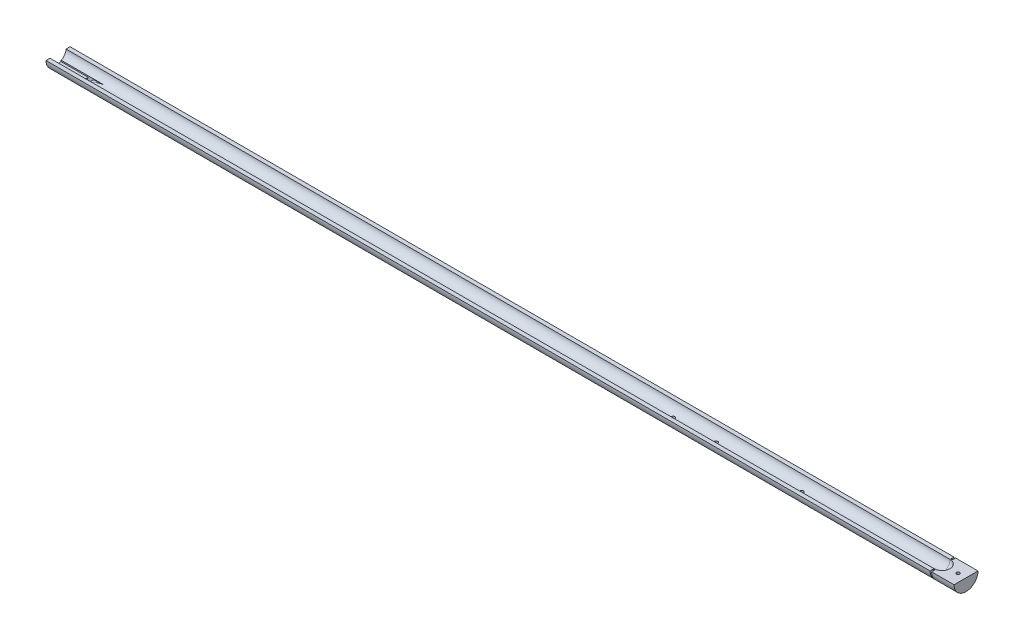
SolidWorks part; units mm, degrees
ref_plane "Front Plane" through (0, 0, 0) normal (0, 0, 1) x (1, 0, 0)
ref_plane "Top Plane" through (0, 0, 0) normal (0, 1, 0) x (1, 0, 0)
ref_plane "Right Plane" through (0, 0, 0) normal (1, 0, 0) x (0, 0, -1)
sketch "Sketch1" plane through (0, 0, 0) normal (0, 1, 0) x (1, 0, 0)
  line L1 (0, 0) -> (1803.4, 0)
  line L2 (0, 0) -> (0, 57.15)
  line L3 (0, 57.15) -> (1803.4, 57.15)
  line L4 (1803.4, 0) -> (1803.4, 57.15)
  dimension "D1" = 1803.4
  dimension "D2" = 57.15
extrude "wood block" add sketch "Sketch1" along normal blind 28.575
ref_plane "Plane1" through (0, 0, -28.575) normal (0, 0, 1) x (1, 0, 0)
sketch "Sketch2" plane through (0, 0, -28.575) normal (0, 0, 1) x (1, 0, 0)
  line L0 (1771.65, 28.575) -> (-15.875, 28.575)
  line L1 (0, 28.575) -> (1803.4, 28.575) construction
  line L2 (0, 12.7) -> (1755.775, 12.7)
  line L4 (1803.4, 28.575) -> (1803.4, 0) construction
  arc A0 (-15.875, 28.575) -> (0, 12.7) centre (0, 28.575) ccw
  arc A1 (1755.775, 12.7) -> (1771.65, 28.575) centre (1755.775, 28.575) ccw
  point P10 (0, 12.7)
  dimension "D1" = 15.875
  dimension "extralength" = 31.75
revolve "Inner Bore" cut sketch "Sketch2" angle 360 about L0
ref_axis "Axis1" through (0, 28.575, -28.575) along (1, 0, 0)
sketch "Sketch5" plane through (0, 0, -28.575) normal (0, 0, 1) x (1, 0, 0)
  line L0 (53.975, 28.575) -> (53.975, 12.1285)
  line L1 (0, 12.7) -> (1755.775, 12.7) construction
  line L3 (53.975, 0) -> (64.135, 0)
  line L4 (64.135, 0) -> (64.135, 12.1285) construction
  line L6 (64.135, 28.575) -> (53.975, 28.575)
  line L10 (0, 4.7625) -> (159.6887, 4.7625) construction
  line L12 (0, 12.7) -> (159.6887, 12.7) construction
  line L13 (64.135, 12.1285) -> (97.4578, 0)
  line L14 (97.4578, 0) -> (64.135, 0)
  line L15 (64.135, 12.1285) -> (64.135, 28.575)
  line L16 (53.975, 12.1285) -> (48.9512, 0)
  line L17 (48.9512, 0) -> (53.975, 0)
  line L18 (53.975, 12.1285) -> (53.975, 0) construction
  line L29 (0, 0) -> (1803.4, 0) construction
  line L34 (0, 28.575) -> (0, 0) construction
  line L35 (0, 28.575) -> (1803.4, 28.575) construction
  line L36 (0, 0) -> (1803.4, 0) construction
  line L37 (64.135, 12.1285) -> (53.975, 12.1285) construction
  point P2 (53.975, 28.575)
  point P3 (53.975, 12.7)
  point P4 (0, 0)
  point P5 (159.6887, 12.7)
  point P6 (1755.775, 28.575)
  point P11 (0, 28.575)
  point P12 (1803.4, 28.575)
  point P21 (53.975, 28.575)
  point P22 (1771.65, 28.575)
  point P23 (1755.775, 28.575)
  point P24 (53.975, 28.575)
  point P25 (38.1, 28.575)
  point P26 (53.975, 28.575)
  point P27 (1755.775, 28.575)
  point P28 (0, 28.575)
  point P29 (0, 0)
  point P30 (1803.4, 28.575)
  point P31 (1803.4, 0)
  point P32 (1803.4, 28.575)
  point P33 (1803.4, 0)
  point P34 (0, 28.575)
  point P35 (0, 0)
  point P36 (1803.4, 28.575)
  point P37 (0, 28.575)
  point P38 (1803.4, 0)
  point P39 (0, 0)
  point P40 (0, 0)
  point P41 (1803.4, 0)
  point P42 (1755.775, 28.575)
  point P43 (1755.775, 12.7)
  point P46 (1755.775, 28.575)
  point P47 (53.975, 28.575)
  point P48 (1771.65, 28.575)
  point P49 (1755.775, 28.575)
  point P50 (53.975, 28.575)
  point P51 (38.1, 28.575)
  point P52 (53.975, 28.575)
  point P53 (1755.775, 28.575)
  dimension "D1" = 10.16
  dimension "D2" = 53.975
  dimension "D3" = 22.5
  dimension "D4" = 20
  dimension "D5" = 7.366
  dimension "D6" = 23.8125
extrude "fipple" cut sketch "Sketch5" against normal mid plane 12.7
sketch "Sketch3" plane through (0, 0, 0) normal (0, 1, 0) x (1, 0, 0)
  line L122 (64.135, 34.925) -> (64.135, 22.225) construction
  line L123 (1476.629, 28.575) -> (1306.449, 28.575) construction
  line L124 (1306.449, 28.575) -> (1221.359, 28.575) construction
  line L125 (1221.359, 28.575) -> (64.135, 28.575) construction
  circle A0 centre (1476.629, 28.575) radius 3.81
  circle A1 centre (1306.449, 28.575) radius 3.81
  circle A2 centre (1221.359, 28.575) radius 3.81
  point P2 (-6.496, 28.575)
  point P3 (6.496, 28.575)
  point P10 (53.975, 22.225)
  point P11 (74.081, 22.225)
  point P12 (53.975, 34.925)
  point P13 (64.135, 34.925)
  point P14 (64.135, 34.925)
  point P15 (64.135, 22.225)
  point P16 (53.975, 22.225)
  point P17 (64.135, 22.225)
  point P18 (1724.025, 44.45)
  point P19 (53.975, 44.45)
  point P20 (1724.025, 28.575)
  point P21 (1724.025, 12.7)
  point P22 (1724.025, 44.45)
  point P23 (53.975, 28.575)
  point P24 (53.975, 44.45)
  point P25 (53.975, 12.7)
  point P26 (53.975, 12.7)
  point P27 (1724.025, 12.7)
  point P28 (1803.4, 4.7625)
  point P29 (1803.4, 52.3875)
  point P30 (0, 52.3875)
  point P31 (0, 4.7625)
  point P32 (53.975, 12.7)
  point P33 (53.975, 22.225)
  point P34 (53.975, 22.225)
  point P35 (53.975, 34.925)
  point P36 (53.975, 34.925)
  point P37 (53.975, 44.45)
  point P38 (1724.025, 12.7)
  point P39 (1724.025, 44.45)
  point P40 (64.135, 34.925)
  point P41 (64.135, 22.225)
  point P42 (74.081, 34.925)
  point P43 (64.135, 34.925)
  point P44 (74.081, 22.225)
  point P45 (64.135, 22.225)
  point P46 (1803.4, 4.7625)
  point P47 (0, 4.7625)
  point P48 (0, 52.3875)
  point P49 (1803.4, 52.3875)
  point P50 (53.975, 34.925)
  point P51 (74.081, 34.925)
  point P52 (74.081, 22.225)
  point P53 (74.081, 34.925)
  point P54 (-54.3985, 28.575)
  point P55 (76.4501, 28.575)
  point P56 (11.0258, 4.7625)
  point P57 (11.0258, 52.3875)
  point P58 (11.0258, 28.575)
  point P59 (53.975, 22.225)
  point P60 (53.975, 34.925)
  point P61 (1803.4, 4.7625)
  point P62 (1803.4, 52.3875)
  point P63 (0, 52.3875)
  point P64 (0, 4.7625)
  point P65 (0, 0)
  point P66 (1803.4, 0)
  point P67 (0, 0)
  point P68 (0, 57.15)
  point P69 (0, 57.15)
  point P70 (1803.4, 57.15)
  point P71 (1803.4, 0)
  point P72 (1803.4, 57.15)
  point P73 (1739.9, 28.575)
  point P74 (38.1, 28.575)
  point P75 (0, 28.575)
  point P76 (1803.4, 28.575)
  point P77 (53.975, 28.575)
  point P78 (1724.025, 28.575)
  point P79 (1803.4, 28.575)
  point P80 (0, 28.575)
  point P81 (53.975, 28.575)
  point P82 (64.135, 28.575)
  point P83 (64.135, 28.575)
  point P84 (53.975, 28.575)
  point P85 (0, 28.575)
  point P86 (1803.4, 28.575)
  point P87 (0, 28.575)
  point P88 (159.6887, 28.575)
  point P89 (0, 28.575)
  point P90 (159.6887, 28.575)
  point P91 (64.135, 28.575)
  point P92 (89.535, 28.575)
  point P93 (89.535, 28.575)
  point P94 (64.135, 28.575)
  point P95 (0, 57.15)
  point P96 (0, 0)
  point P97 (-13.0969, 0)
  point P98 (13.0969, 0)
  point P99 (0, -13.0969)
  point P100 (0, 13.0969)
  point P101 (53.975, 22.225)
  point P102 (74.081, 22.225)
  point P103 (53.975, 34.925)
  point P104 (64.135, 34.925)
  point P105 (64.135, 34.925)
  point P106 (64.135, 22.225)
  point P107 (53.975, 22.225)
  point P108 (64.135, 22.225)
  point P109 (1724.025, 44.45)
  point P110 (53.975, 44.45)
  point P111 (1724.025, 28.575)
  point P112 (1724.025, 12.7)
  point P113 (1724.025, 44.45)
  point P114 (53.975, 28.575)
  point P115 (53.975, 44.45)
  point P116 (53.975, 12.7)
  point P117 (53.975, 12.7)
  point P118 (1724.025, 12.7)
  point P119 (1803.4, 4.7625)
  point P120 (1803.4, 52.3875)
  point P121 (0, 52.3875)
  point P122 (0, 4.7625)
  point P123 (53.975, 12.7)
  point P124 (53.975, 22.225)
  point P125 (53.975, 22.225)
  point P126 (53.975, 34.925)
  point P127 (53.975, 34.925)
  point P128 (53.975, 44.45)
  point P129 (1724.025, 12.7)
  point P130 (1724.025, 44.45)
  point P131 (64.135, 34.925)
  point P132 (64.135, 22.225)
  point P133 (74.081, 34.925)
  point P134 (64.135, 34.925)
  point P135 (74.081, 22.225)
  point P136 (64.135, 22.225)
  point P137 (1803.4, 4.7625)
  point P138 (0, 4.7625)
  point P139 (0, 52.3875)
  point P140 (1803.4, 52.3875)
  point P141 (53.975, 34.925)
  point P142 (74.081, 34.925)
  point P143 (74.081, 22.225)
  point P144 (74.081, 34.925)
  point P145 (-54.3985, 28.575)
  point P146 (76.4501, 28.575)
  point P147 (11.0258, 4.7625)
  point P148 (11.0258, 52.3875)
  point P149 (11.0258, 28.575)
  point P150 (53.975, 22.225)
  point P151 (53.975, 34.925)
  point P152 (1803.4, 4.7625)
  point P153 (1803.4, 52.3875)
  point P154 (0, 52.3875)
  point P155 (0, 4.7625)
  point P156 (0, 0)
  point P157 (1803.4, 0)
  point P158 (0, 0)
  point P159 (0, 57.15)
  point P160 (0, 57.15)
  point P161 (1803.4, 57.15)
  point P162 (1803.4, 0)
  point P163 (1803.4, 57.15)
  point P164 (1739.9, 28.575)
  point P165 (38.1, 28.575)
  point P166 (0, 28.575)
  point P167 (1803.4, 28.575)
  point P168 (53.975, 28.575)
  point P169 (1724.025, 28.575)
  point P170 (1803.4, 28.575)
  point P171 (0, 28.575)
  point P172 (53.975, 28.575)
  point P173 (64.135, 28.575)
  point P174 (64.135, 28.575)
  point P175 (53.975, 28.575)
  point P176 (0, 28.575)
  point P177 (1803.4, 28.575)
  point P178 (0, 28.575)
  point P179 (159.6887, 28.575)
  point P180 (0, 28.575)
  point P181 (159.6887, 28.575)
  point P182 (64.135, 28.575)
  point P183 (89.535, 28.575)
  point P184 (89.535, 28.575)
  point P185 (64.135, 28.575)
  point P186 (0, 57.15)
  point P187 (0, 0)
  point P188 (-13.0969, 0)
  point P189 (13.0969, 0)
  point P190 (0, -13.0969)
  point P191 (0, 13.0969)
  point P192 (-6.496, 28.575)
  point P193 (6.496, 28.575)
  point P194 (53.975, 22.225)
  point P195 (74.081, 22.225)
  point P196 (53.975, 34.925)
  point P197 (64.135, 34.925)
  point P198 (64.135, 34.925)
  point P199 (64.135, 22.225)
  point P200 (53.975, 22.225)
  point P201 (64.135, 22.225)
  point P202 (1724.025, 44.45)
  point P203 (53.975, 44.45)
  point P204 (1724.025, 28.575)
  point P205 (1724.025, 12.7)
  point P206 (1724.025, 44.45)
  point P207 (53.975, 28.575)
  point P208 (53.975, 44.45)
  point P209 (53.975, 12.7)
  point P210 (53.975, 12.7)
  point P211 (1724.025, 12.7)
  point P212 (1803.4, 4.7625)
  point P213 (1803.4, 52.3875)
  point P214 (0, 52.3875)
  point P215 (0, 4.7625)
  point P216 (53.975, 12.7)
  point P217 (53.975, 22.225)
  point P218 (53.975, 22.225)
  point P219 (53.975, 34.925)
  point P220 (53.975, 34.925)
  point P221 (53.975, 44.45)
  point P222 (1724.025, 12.7)
  point P223 (1724.025, 44.45)
  point P224 (64.135, 34.925)
  point P225 (64.135, 22.225)
  point P226 (74.081, 34.925)
  point P227 (64.135, 34.925)
  point P228 (74.081, 22.225)
  point P229 (64.135, 22.225)
  point P230 (1803.4, 4.7625)
  point P231 (0, 4.7625)
  point P232 (0, 52.3875)
  point P233 (1803.4, 52.3875)
  point P234 (53.975, 34.925)
  point P235 (74.081, 34.925)
  point P236 (74.081, 22.225)
  point P237 (74.081, 34.925)
  point P238 (-54.3985, 28.575)
  point P239 (76.4501, 28.575)
  point P240 (11.0258, 4.7625)
  point P241 (11.0258, 52.3875)
  point P242 (11.0258, 28.575)
  point P243 (53.975, 22.225)
  point P244 (53.975, 34.925)
  point P245 (1803.4, 4.7625)
  point P246 (1803.4, 52.3875)
  point P247 (0, 52.3875)
  point P248 (0, 4.7625)
  point P249 (0, 0)
  point P250 (1803.4, 0)
  point P251 (0, 0)
  point P252 (0, 57.15)
  point P253 (0, 57.15)
  point P254 (1803.4, 57.15)
  point P255 (1803.4, 0)
  point P256 (1803.4, 57.15)
  point P257 (1739.9, 28.575)
  point P258 (38.1, 28.575)
  point P259 (0, 28.575)
  point P260 (1803.4, 28.575)
  point P261 (53.975, 28.575)
  point P262 (1724.025, 28.575)
  point P263 (1803.4, 28.575)
  point P264 (0, 28.575)
  point P265 (53.975, 28.575)
  point P266 (64.135, 28.575)
  point P267 (64.135, 28.575)
  point P268 (53.975, 28.575)
  point P269 (0, 28.575)
  point P270 (1803.4, 28.575)
  point P271 (0, 28.575)
  point P272 (159.6887, 28.575)
  point P273 (0, 28.575)
  point P274 (159.6887, 28.575)
  point P275 (64.135, 28.575)
  point P276 (89.535, 28.575)
  point P277 (89.535, 28.575)
  point P278 (64.135, 28.575)
  point P279 (0, 57.15)
  point P280 (0, 0)
  point P281 (-13.0969, 0)
  point P282 (13.0969, 0)
  point P283 (0, -13.0969)
  point P284 (0, 13.0969)
  point P285 (-6.496, 28.575)
  point P286 (6.496, 28.575)
  dimension "D1" = 7.62
  dimension "D2" = 7.62
  dimension "D3" = 7.62
  dimension "D5" = 1242.314
  dimension "D4" = 1157.224
  dimension "D6" = 1412.494
extrude "finger holes" cut sketch "Sketch3" along normal through all
sketch "Sketch9" plane through (0, 0, -28.575) normal (0, 0, 1) x (1, 0, 0)
  line L0 (64.135, 12.3825) -> (84.3737, 14.1532)
  line L1 (64.135, 12.1285) -> (64.135, 14.0253) construction
  line L2 (84.3737, 14.1532) -> (64.135, 16.8013)
  line L3 (64.135, 16.8013) -> (64.135, 12.3825)
  line L4 (1803.4, 28.575) -> (0, 28.575) construction
  point P4 (64.135, 12.5112)
  point P9 (84.3737, 14.2802)
  point P10 (64.135, 16.8013)
  dimension "D1" = 0.254
  dimension "D2" = 5
extrude "fipple inside chamfer" cut sketch "Sketch9" against normal mid plane 12.7
sketch "Sketch8" plane through (0, 0, 0) normal (-1, 0, 0) x (0, 0, 1)
  line L0 (-28.575, 28.575) -> (-28.575, 14.8425) construction
  line L1 (-12.7, 28.575) -> (-44.45, 28.575) construction
  line L2 (-34.925, 14.0253) -> (-34.925, 12.1285) construction
  line L3 (-22.225, 18.19) -> (-34.925, 18.19)
  line L4 (-22.225, 18.19) -> (-22.225, 11.4951)
  line L5 (-22.225, 11.4951) -> (-34.925, 11.4951)
  line L6 (-34.925, 18.19) -> (-34.925, 11.4951)
  line L7 (-22.225, 18.19) -> (-34.925, 11.4951) construction
  line L8 (-22.225, 11.4951) -> (-34.925, 18.19) construction
  line L10 (-22.225, 12.3333) -> (-34.925, 12.3333) construction
  dimension "D1" = 0.8382
extrude "flue" cut sketch "Sketch8" against normal blind 58.42
sketch "Sketch10" plane through (0, 28.575, 0) normal (0, 1, 0) x (1, 0, 0)
  line L0 (1803.4, 28.575) -> (1787.525, 28.575) construction
  line L1 (1803.4, 0) -> (1803.4, 57.15) construction
  circle A2 centre (1787.525, 28.575) radius 3.175
  dimension "D2" = 6.35
  dimension "D1" = 15.875
extrude "dowel pin hole" cut sketch "Sketch10" against normal blind 15.24
sketch "Sketch6" plane through (0, 0, 0) normal (-1, 0, 0) x (0, 0, 1)
  line L1 (-12.7, 28.575) -> (-44.45, 28.575) construction
  circle A0 centre (-28.575, 28.575) radius 23.8125
  point P2 (-28.575, 28.575)
  point P4 (-50.8, 28.575)
  dimension "D1" = 47.625
extrude "outside diameter" cut sketch "Sketch6" against normal through all flip side to cut
sketch "Sketch11" plane through (0, 28.575, 0) normal (0, 1, 0) x (1, 0, 0)
  line L0 (1755.775, 4.7625) -> (1755.775, 12.7) construction
  line L1 (1803.4, 4.7625) -> (0, 4.7625) construction
  line L3 (1755.775, 4.7625) -> (1758.95, 4.7625)
  line L4 (1755.775, 4.7625) -> (1755.775, 11.1125)
  line L5 (1755.775, 11.1125) -> (1758.95, 11.1125)
  line L6 (1758.95, 4.7625) -> (1758.95, 11.1125)
  dimension "D1" = 3.175
  dimension "D2" = 6.35
revolve "end length locator" cut sketch "Sketch11" angle 360 about axis through (0, 28.575, -28.575) along (1, 0, 0)
